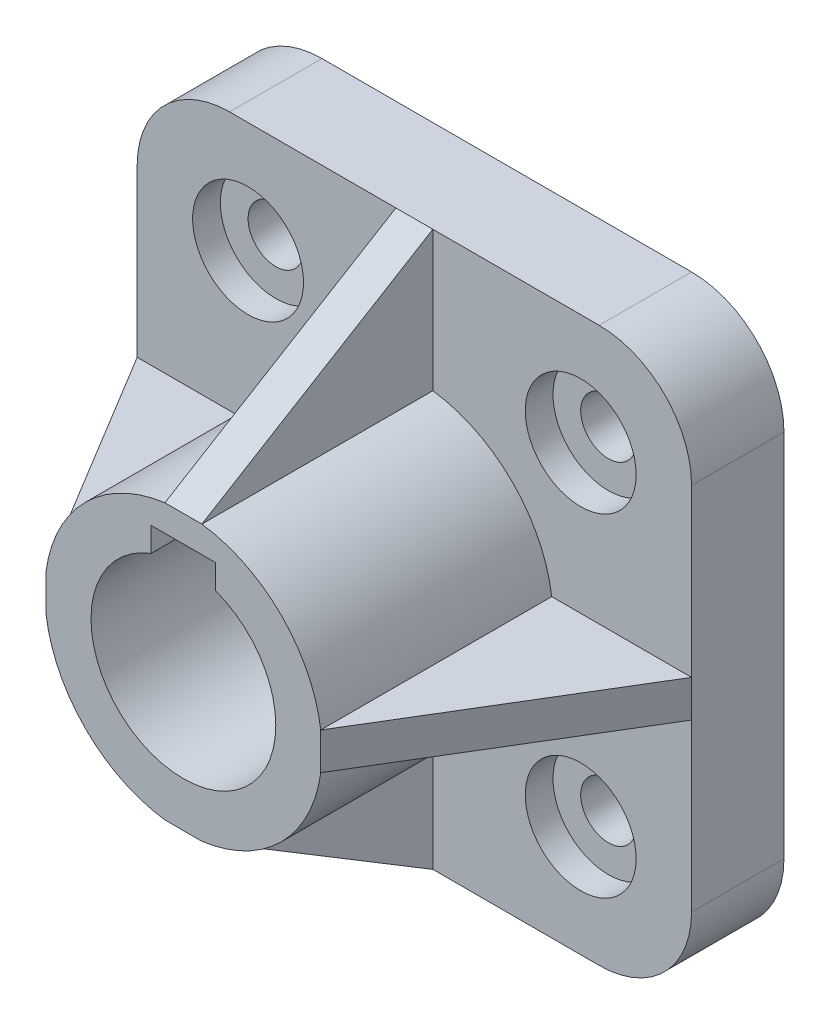
SolidWorks part; units mm, degrees
ref_plane "Ön Düzlem" through (0, 0, 0) normal (0, 0, 1) x (1, 0, 0)
ref_plane "Üst Düzlem" through (0, 0, 0) normal (0, 1, 0) x (1, 0, 0)
ref_plane "Sağ Düzlem" through (0, 0, 0) normal (1, 0, 0) x (0, 0, -1)
sketch "Çizim1" plane through (0, 0, 0) normal (0, 0, 1) x (1, 0, 0)
  line L1 (40, -60) -> (-40, -60)
  line L2 (60, -40) -> (60, 40)
  line L3 (40, 60) -> (-40, 60)
  line L4 (-60, -40) -> (-60, 40)
  line L5 (60, -60) -> (-60, 60) construction
  line L6 (60, 60) -> (-60, -60) construction
  arc A0 (-40, -60) -> (-60, -40) centre (-40, -40) cw
  arc A1 (40, -60) -> (60, -40) centre (40, -40) ccw
  arc A2 (60, 40) -> (40, 60) centre (40, 40) ccw
  arc A3 (-60, 40) -> (-40, 60) centre (-40, 40) cw
  point P0 (0, 0)
  dimension "D3" = 20
  dimension "D1" = 120
  dimension "D2" = 120
extrude "Yükseklik-Ekstrüzyon1" add sketch "Çizim1" along normal blind 20
sketch "Çizim2" plane through (0, 0, 20) normal (0, 0, 1) x (1, 0, 0)
  line L1 (36, -36) -> (-36, -36)
  line L2 (36, -36) -> (36, 36)
  line L3 (36, 36) -> (-36, 36)
  line L4 (-36, -36) -> (-36, 36)
  line L5 (36, -36) -> (-36, 36) construction
  line L6 (36, 36) -> (-36, -36) construction
  circle A0 centre (-36, 36) radius 12
  circle A1 centre (36, 36) radius 12
  circle A2 centre (-36, -36) radius 12
  circle A3 centre (36, -36) radius 12
  point P0 (0, 0)
  dimension "D3" = 24
  dimension "D4" = 24
  dimension "D5" = 24
  dimension "D6" = 24
  dimension "D1" = 72
  dimension "D2" = 72
extrude "Kes-Ekstrüzyon1" cut sketch "Çizim2" against normal blind 6 contours A0 | A1 | A2 | A3
sketch "Çizim3" plane through (0, 0, 20) normal (0, 0, 1) x (1, 0, 0)
  circle A0 centre (-36, 36) radius 6
  circle A1 centre (36, 36) radius 6
  circle A2 centre (36, -36) radius 6
  circle A3 centre (-36, -36) radius 6
  dimension "D1" = 12
  dimension "D2" = 12
  dimension "D3" = 12
  dimension "D4" = 12
extrude "Kes-Ekstrüzyon2" cut sketch "Çizim3" against normal through all
sketch "Çizim4" plane through (0, 0, 20) normal (0, 0, 1) x (1, 0, 0)
  line L0 (40, 60) -> (-40, 60) construction
  line L1 (4, -60) -> (-4, -60)
  line L2 (4, -60) -> (4, -29.7321)
  line L3 (4, 60) -> (-4, 60)
  line L4 (-4, -60) -> (-4, -29.7321)
  line L7 (60, -40) -> (60, 40) construction
  line L8 (-60, -4) -> (-29.7321, -4)
  line L9 (-60, -4) -> (-60, 4)
  line L10 (-60, 4) -> (-29.7321, 4)
  line L11 (60, -4) -> (60, 4)
  line L14 (4, 29.7321) -> (4, 60)
  line L17 (-4, 29.7321) -> (-4, 60)
  line L26 (29.7321, -4) -> (60, -4)
  line L29 (29.7321, 4) -> (60, 4)
  arc A0 (-4, 29.7321) -> (-29.7321, 4) centre (0, 0) ccw
  arc A1 (-29.7321, -4) -> (-4, -29.7321) centre (0, 0) ccw
  arc A2 (29.7321, 4) -> (4, 29.7321) centre (0, 0) ccw
  arc A3 (4, -29.7321) -> (29.7321, -4) centre (0, 0) ccw
  dimension "D1" = 60
  dimension "D2" = 8
  dimension "D3" = 8
extrude "Yükseklik-Ekstrüzyon2" add sketch "Çizim4" along normal blind 50
sketch "Çizim5" plane through (0, 0, 70) normal (0, 0, 1) x (1, 0, 0)
  line L0 (7, 18.735) -> (7, 24)
  line L3 (7, 24) -> (-7, 24)
  line L9 (-7, 18.735) -> (-7, 24)
  arc A0 (-7, 18.735) -> (7, 18.735) centre (0, 0) ccw
  point P7 (0, 0)
  dimension "D1" = 40
  dimension "D2" = 14
  dimension "D3" = 24
extrude "Kes-Ekstrüzyon3" cut sketch "Çizim5" against normal through all
sketch "Çizim6" plane through (-4, 0, 0) normal (-1, 0, 0) x (0, 0, 1)
  line L0 (70, 60) -> (70, 29.7321)
  line L1 (70, 29.7321) -> (20, 60)
  line L2 (20, 60) -> (70, 60)
extrude "Kes-Ekstrüzyon4" cut sketch "Çizim6" against normal through all
sketch "Çizim7" plane through (-4, 0, 0) normal (-1, 0, 0) x (0, 0, 1)
  line L0 (70, -29.7321) -> (20, -60)
  line L1 (20, -60) -> (70, -60)
  line L2 (70, -60) -> (70, -29.7321)
extrude "Kes-Ekstrüzyon5" cut sketch "Çizim7" against normal through all
sketch "Çizim8" plane through (0, 4, 0) normal (0, 1, 0) x (1, 0, 0)
  line L0 (-60, -20) -> (-29.7321, -70)
  line L1 (-29.7321, -70) -> (-60, -70)
  line L2 (-60, -70) -> (-60, -20)
  line L3 (60, -20) -> (29.7321, -70)
  line L4 (29.7321, -70) -> (60, -70)
  line L5 (60, -70) -> (60, -20)
extrude "Kes-Ekstrüzyon6" cut sketch "Çizim8" against normal through all
